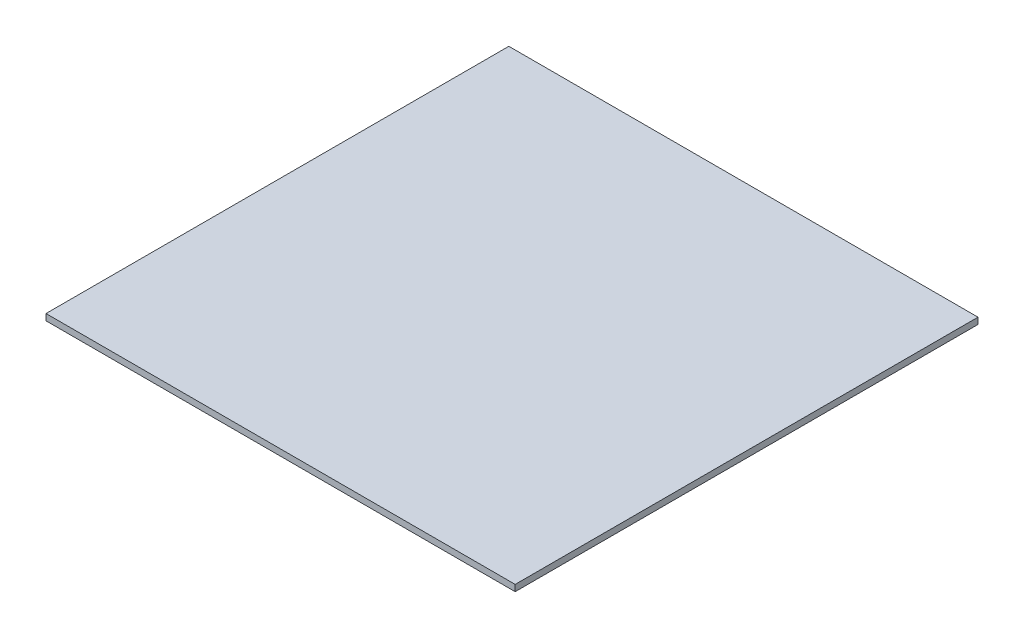
SolidWorks part; units mm, degrees
ref_plane "Front Plane" through (0, 0, 0) normal (0, 0, 1) x (1, 0, 0)
ref_plane "Top Plane" through (0, 0, 0) normal (0, 1, 0) x (1, 0, 0)
ref_plane "Right Plane" through (0, 0, 0) normal (1, 0, 0) x (0, 0, -1)
sketch "Sketch1" plane through (0, 0, 0) normal (0, 1, 0) x (1, 0, 0)
  line L1 (-37, 36.5) -> (37, 36.5)
  line L2 (-37, 36.5) -> (-37, -36.5)
  line L3 (-37, -36.5) -> (37, -36.5)
  line L4 (37, 36.5) -> (37, -36.5)
extrude "Boss-Extrude1" add sketch "Sketch1" along normal blind 1
